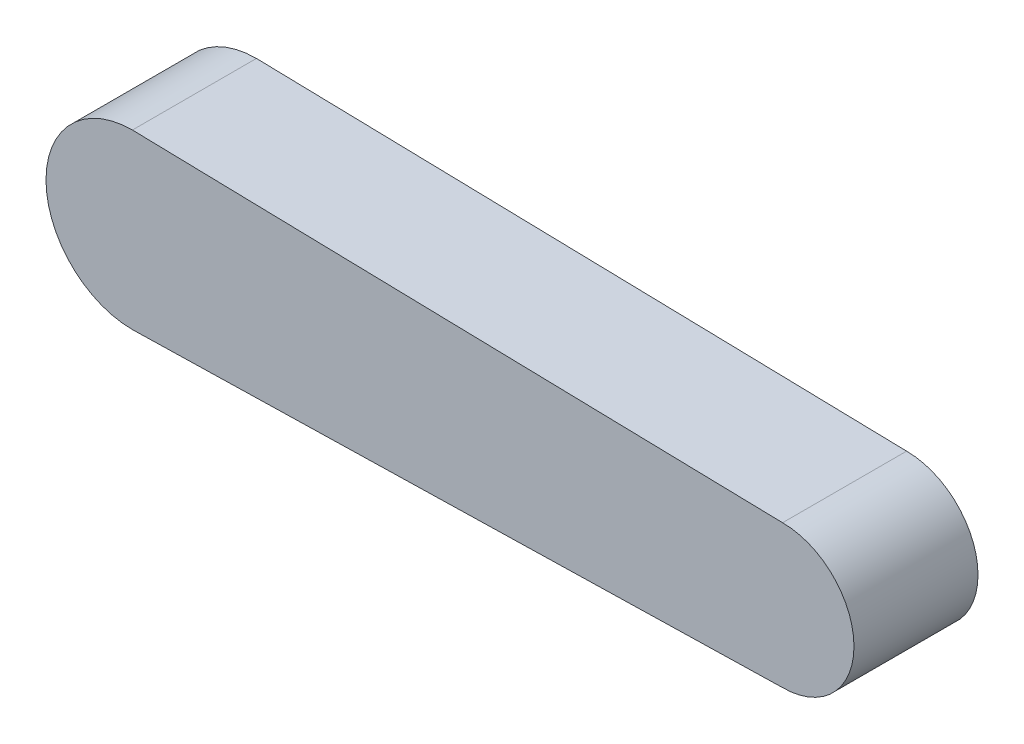
SolidWorks part; units mm, degrees
ref_plane "Front Plane" through (0, 0, 0) normal (0, 0, 1) x (1, 0, 0)
ref_plane "Top Plane" through (0, 0, 0) normal (0, 1, 0) x (1, 0, 0)
ref_plane "Right Plane" through (0, 0, 0) normal (1, 0, 0) x (0, 0, -1)
sketch "Sketch1" plane through (0, 0, 0) normal (0, 0, 1) x (1, 0, 0)
  line L0 (0, 2.3) -> (17.3, 1.9)
  line L1 (0, -2.3) -> (17.3, -1.9)
  arc A0 (0, 2.3) -> (0, -2.3) centre (0, 0) ccw
  arc A1 (17.3, -1.9) -> (17.3, 1.9) centre (17.3, 0) ccw
  point P1 (0, 0)
  point P4 (0, 0)
  dimension "D1" = 2.3
  dimension "D2" = 1.9
  dimension "D3" = 17.3
extrude "Boss-Extrude2" add sketch "Sketch1" along normal blind 3.3
